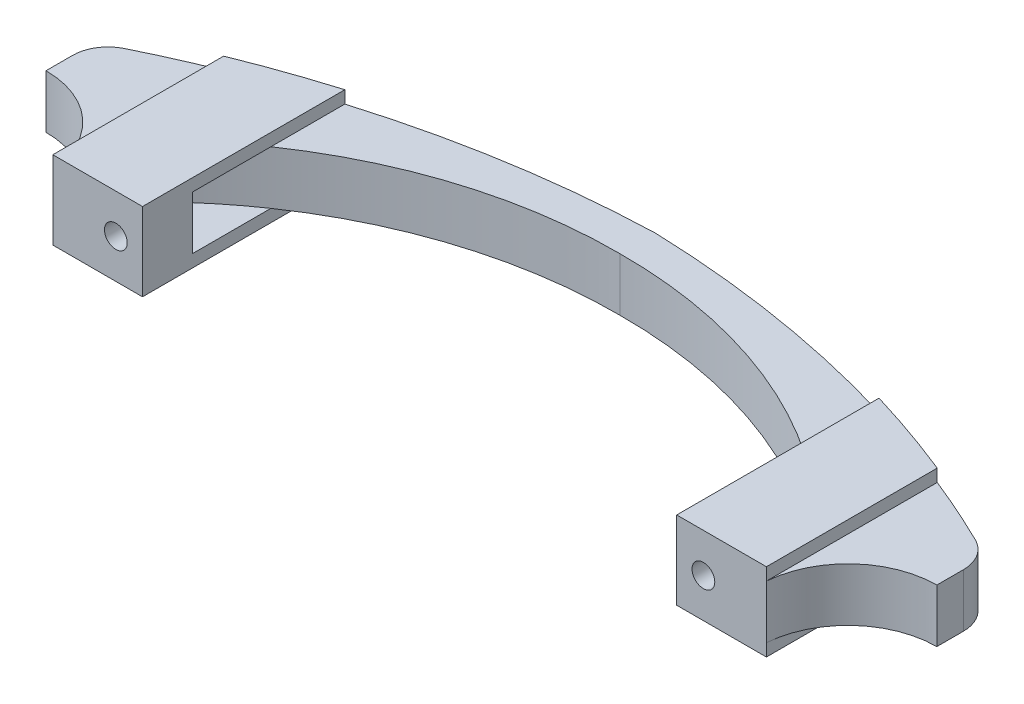
SolidWorks part; units mm, degrees
material "ABS"
ref_plane "Front Plane" through (0, 0, 0) normal (0, 0, 1) x (1, 0, 0)
ref_plane "Top Plane" through (0, 0, 0) normal (0, 1, 0) x (1, 0, 0)
ref_plane "Right Plane" through (0, 0, 0) normal (1, 0, 0) x (0, 0, -1)
sketch "Sketch1" plane through (0, 0, 0) normal (0, 1, 0) x (1, 0, 0)
  line L0 (-50.125, 0) -> (-37.555, 0)
  line L1 (-50.125, 0) -> (-62.625, 0)
  line L2 (-37.555, 0) -> (-37.555, 8)
  line L3 (-37.555, 8) -> (-45.055, 8)
  line L4 (-62.625, 0) -> (-62.625, 12.5)
  line L5 (-62.625, 12.5) -> (-62.625, 19.3056)
  line L6 (-45.055, 8) -> (-53.0203, 8)
  circle A0 centre (-62.625, 0) radius 12.5
  circle A1 centre (0, 0) radius 50.125
  circle A3 centre (-62.625, 0) radius 19.3056
  dimension "D1" = 100.25
  dimension "D2" = 12.5
  dimension "D3" = 12.57
  dimension "D4" = 8
  dimension "D5" = 7.5
extrude "Boss-Extrude1" add sketch "Sketch1" along normal blind 7.5 contours A1 L6 A0 | L0 A3 L6 A1 | A3 L0 L2 L3 | L6 A3 A1 | A1 A3 L5 A0 L6
sketch "Sketch2" plane through (0, 0, -8) normal (0, 0, -1) x (-1, 0, 0)
  line L0 (45.055, 3.75) -> (41.305, 3.75)
  line L3 (45.055, 7.5) -> (45.055, 0) construction
  circle A1 centre (41.305, 3.75) radius 1.6
  dimension "D1" = 3.75
  dimension "D2" = 3.2
extrude "Cut-Extrude1" cut sketch "Sketch2" against normal through all
sketch "Sketch3" plane through (0, 7.5, 0) normal (0, 1, 0) x (1, 0, 0)
  line L0 (-37.555, 8) -> (-37.555, 11.25)
  line L1 (-37.555, 11.25) -> (-46.9361, 11.25)
  line L4 (-37.555, 11.25) -> (0, 11.25)
  line L5 (0, 11.25) -> (0, 30.57)
  line L6 (0, 30.57) -> (0, 35.57)
  line L7 (-62.625, 12.5) -> (-62.625, 19.3056) construction
  arc A0 (-45.055, 8) -> (-62.625, 19.3056) centre (-62.625, 0) ccw construction
  arc A2 (-46.9361, 11.25) -> (0, 30.57) centre (-0.3584, -35.2326) cw
  arc A3 (-62.625, 19.3056) -> (0, 35.57) centre (4.6126, -110.8891) cw
  arc A4 (-46.9361, 11.25) -> (-62.625, 19.3056) centre (-62.625, 0) ccw
  arc M10 (-45.055, 8) -> (-62.625, 19.3056) centre (-62.625, 0) ccw
  dimension "D1" = 3.25
  dimension "D2" = 37.555
  dimension "D3" = 19.32
  dimension "D4" = 5
extrude "Boss-Extrude4" add sketch "Sketch3" against normal up to surface (7.5 mm away) contours A3 A2 L6 M10 up to face at (-48.5483, 0, -8.8294)
sketch "Sketch4" plane through (0, 0, -8) normal (0, 0, -1) x (-1, 0, 0)
  line L1 (44.445, 3.75) -> (42.875, 6.4693)
  line L2 (42.875, 6.4693) -> (39.735, 6.4693)
  line L3 (39.735, 6.4693) -> (38.165, 3.75)
  line L4 (38.165, 3.75) -> (39.735, 1.0307)
  line L5 (39.735, 1.0307) -> (42.875, 1.0307)
  line L6 (42.875, 1.0307) -> (44.445, 3.75)
  circle A0 centre (41.305, 3.75) radius 3.15
  circle A1 centre (41.305, 3.75) radius 2.7193 construction
  circle M1 centre (41.305, 3.75) radius 1.6
  dimension "D1" = 6.3
extrude "Cut-Extrude2" cut sketch "Sketch4" against normal blind 2.6 contours L5 L6 L1 L2 L3 L4 M1
ref_plane "Plane2" through (0, 0, 0) normal (1, 0, 0) x (0, 0, -1)
mirror "Mirror5" about plane through (0, 0, 0) normal (1, 0, 0) of "Boss-Extrude4"
mirror "Mirror6" about plane through (0, 0, 0) normal (1, 0, 0) of "Boss-Extrude1"
mirror "Mirror7" about plane through (0, 0, 0) normal (1, 0, 0) of "Cut-Extrude2", "Cut-Extrude1"
sketch "Sketch6" plane through (0, 0, 0) normal (0, 0, 1) x (1, 0, 0)
  circle A0 centre (0, 0) radius 156.1764
extrude "Cut-Extrude3" cut sketch "Sketch6" against normal blind 1
fillet "Fillet1" radius 5 1 edges at (-62.625, 3.75, -19.3056)
fillet "Fillet2" radius 5 1 edges at (62.625, 3.75, -19.3056)
fillet "Fillet3" radius 5 1 edges at (-46.9361, 3.75, -11.25)
fillet "Fillet4" radius 5 1 edges at (46.9361, 3.75, -11.25)
sketch "Sketch7" plane through (0, 7.5, 0) normal (0, 1, 0) x (1, 0, 0)
  line L0 (-50.1651, 1) -> (-37.555, 1)
  line L1 (-37.555, 1) -> (-37.555, 29.4442)
  line L2 (-50.1651, 1) -> (-50.1651, 25.0188)
  arc A0 (0, 35.57) -> (-59.8237, 20.7145) centre (4.6126, -110.8891) ccw construction
  arc A1 (-50.1651, 25.0188) -> (-37.555, 29.4442) centre (4.6126, -110.8891) cw
extrude "Boss-Extrude5" add sketch "Sketch7" along normal blind 1.75
ref_plane "Plane3" through (0, 3.75, 0) normal (0, 1, 0) x (1, 0, 0)
mirror "Mirror8" about plane through (0, 3.75, 0) normal (0, 1, 0) of "Boss-Extrude5"
mirror "Mirror9" about plane through (0, 0, 0) normal (1, 0, 0) of "Mirror8", "Boss-Extrude5"
